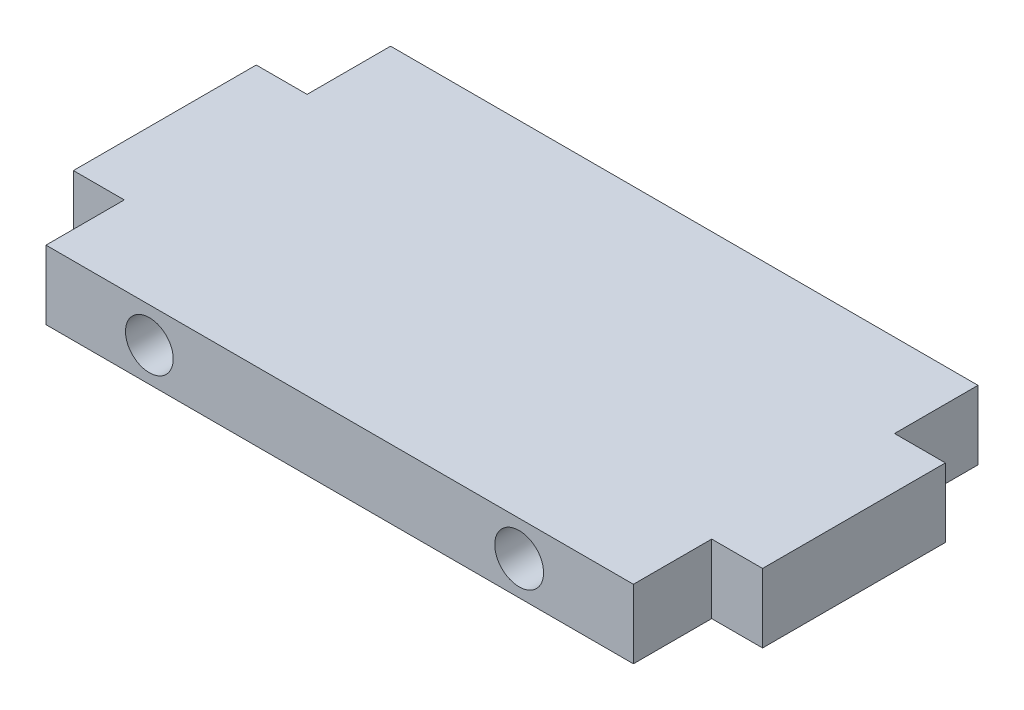
SolidWorks part; units mm, degrees
ref_plane "Front Plane" through (0, 0, 0) normal (0, 0, 1) x (1, 0, 0)
ref_plane "Top Plane" through (0, 0, 0) normal (0, 1, 0) x (1, 0, 0)
ref_plane "Right Plane" through (0, 0, 0) normal (1, 0, 0) x (0, 0, -1)
sketch "Sketch2" plane through (0, 0, 0) normal (0, 1, 0) x (1, 0, 0)
  line L1 (-85.0989, 55.9353) -> (88.1011, 55.9353)
  line L2 (-100.0989, 40.9353) -> (-100.0989, -30.6647)
  line L3 (-85.0989, -45.6647) -> (88.1011, -45.6647)
  line L4 (103.1011, 40.9353) -> (103.1011, -30.6647)
  arc A0 (88.1011, -45.6647) -> (103.1011, -30.6647) centre (88.1011, -30.6647) ccw
  arc A1 (-100.0989, -30.6647) -> (-85.0989, -45.6647) centre (-85.0989, -30.6647) ccw
  arc A2 (-85.0989, 55.9353) -> (-100.0989, 40.9353) centre (-85.0989, 40.9353) ccw
  arc A3 (88.1011, 55.9353) -> (103.1011, 40.9353) centre (88.1011, 40.9353) cw
  point P8 (-100.0989, -45.6647)
  point P11 (-100.0989, 55.9353)
  point P14 (103.1011, 55.9353)
  dimension "D3" = 15
  dimension "D4" = 15
  dimension "D5" = 15
  dimension "D6" = 15
  dimension "D1" = 203.2
  dimension "D2" = 101.6
extrude "Boss-Extrude1" add sketch "Sketch2" against normal blind 20.32
sketch "Sketch3" plane through (0, 0, 0) normal (0, 1, 0) x (1, 0, 0)
  line L0 (-85.0989, -45.6647) -> (88.1011, -45.6647) construction
  line L11 (88.1011, 55.9353) -> (111.6846, 55.9353)
  line L12 (88.1011, 55.9353) -> (88.1011, 31.3221)
  line L13 (88.1011, 31.3221) -> (111.6846, 31.3221)
  line L14 (111.6846, 55.9353) -> (111.6846, 31.3221)
  line L15 (88.1011, -45.6647) -> (111.6846, -45.6647)
  line L16 (88.1011, -45.6647) -> (88.1011, -22.5828)
  line L17 (88.1011, -22.5828) -> (111.6846, -22.5828)
  line L18 (111.6846, -45.6647) -> (111.6846, -22.5828)
  line L19 (-85.0989, 55.9353) -> (-110.9795, 55.9353)
  line L20 (-85.0989, 55.9353) -> (-85.0989, 31.3221)
  line L21 (-85.0989, 31.3221) -> (-110.9795, 31.3221)
  line L22 (-110.9795, 55.9353) -> (-110.9795, 31.3221)
  line L23 (-85.0989, -45.6647) -> (-110.9795, -45.6647)
  line L24 (-85.0989, -45.6647) -> (-85.0989, -22.5828)
  line L25 (-85.0989, -22.5828) -> (-110.9795, -22.5828)
  line L26 (-110.9795, -45.6647) -> (-110.9795, -22.5828)
  arc A2 (-85.0989, 55.9353) -> (-100.0989, 40.9353) centre (-85.0989, 40.9353) ccw construction
  arc A3 (-100.0989, -30.6647) -> (-85.0989, -45.6647) centre (-85.0989, -30.6647) ccw construction
extrude "Cut-Extrude1" cut sketch "Sketch3" against normal through all contours L20 L19 L22 L21 | L24 L23 L26 L25 | L16 L15 L18 L17 | L12 L11 L14 L13
sketch "Sketch4" plane through (0, 0, 45.6647) normal (0, 0, 1) x (1, 0, 0)
  circle A1 centre (54.4106, -10.3131) radius 7.1992
extrude "Cut-Extrude2" cut sketch "Sketch4" against normal through all contours A1
sketch "Sketch5" plane through (0, 0, 45.6647) normal (0, 0, 1) x (1, 0, 0)
  circle A0 centre (54.4106, -10.3131) radius 7.1992
  circle A1 centre (-54.6243, -10.3131) radius 7.0394
extrude "Cut-Extrude4" cut sketch "Sketch5" against normal through all contours A1 | A0
